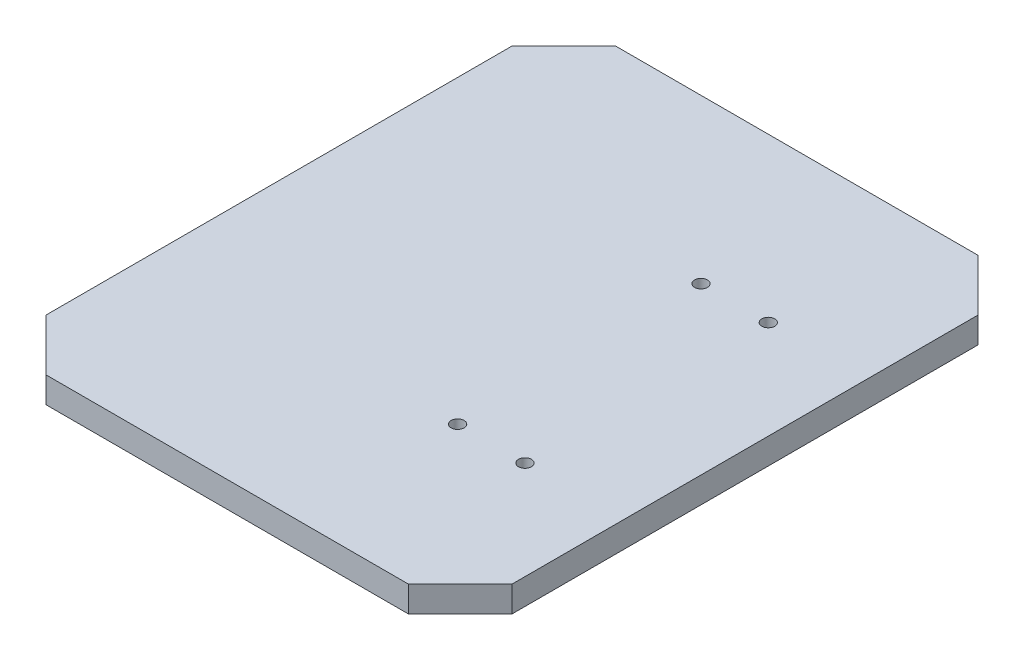
SolidWorks part; units mm, degrees
ref_plane "前视基准面" through (0, 0, 0) normal (0, 0, 1) x (1, 0, 0)
ref_plane "上视基准面" through (0, 0, 0) normal (0, 1, 0) x (1, 0, 0)
ref_plane "右视基准面" through (0, 0, 0) normal (1, 0, 0) x (0, 0, -1)
sketch "草图1" plane through (0, 0, 0) normal (0, 1, 0) x (1, 0, 0)
  line L0 (0, 0) -> (0, 110)
  line L1 (0, 110) -> (90, 110)
  line L2 (90, 110) -> (90, 0)
  line L3 (90, 0) -> (0, 0)
  line L4 (36, 110) -> (36, 0) construction
  line L5 (15, 110) -> (15, 0) construction
  line L6 (0, 55) -> (90, 55) construction
  point P11 (19, 78.5)
  point P12 (32, 78.5)
  point P16 (32, 31.5)
  point P17 (19, 31.5)
  dimension "D1" = 90
  dimension "D2" = 110
  dimension "D3" = 15
  dimension "D4" = 21
  dimension "D5" = 4
  dimension "D6" = 4
  dimension "D7" = 23.5
extrude "凸台-拉伸1" add sketch "草图1" along normal blind 5
chamfer "倒角1" distance 10 distance2 10 4 edges at (0, 2.5, -110) (90, 2.5, -110) (90, 2.5, 0) (0, 2.5, 0)
hole_wizard "M3 螺纹孔1" positions "草图2" profile "草图3" tap size "M3" standard "GB" end condition through all
sketch "草图2" plane through (0, 0, 0) normal (0, -1, 0) x (-1, 0, 0)
  line L1 (-90, 10) -> (-90, 100) construction
  line L2 (-90, 55) -> (0, 55) construction
  line L3 (0, 100) -> (0, 10) construction
  point P0 (-58, 78.5)
  point P2 (-58, 31.5)
  point P4 (-71, 31.5)
  point P6 (-71, 78.5)
  dimension "D1" = 19
  dimension "D2" = 13
  dimension "D3" = 23.5
  dimension "D4" = 23.5
cosmetic thread "孔螺蚊线1" parameters "D2"=3
cosmetic thread "孔螺蚊线2" parameters "D2"=3
cosmetic thread "孔螺蚊线3" parameters "D2"=3
cosmetic thread "孔螺蚊线4" parameters "D2"=3
sketch "草图3" plane through (58, 0, -78.5) normal (1, 0, 0) x (0, 0, -1)
  line L0 (0, 0) -> (0, 5)
  line L1 (0, 5) -> (1.25, 5)
  line L2 (1.25, 5) -> (1.25, 0)
  line L5 (1.25, 0) -> (0, 0)
  line L11 (0, -6.35) -> (0, 107.95) construction
  dimension "通孔螺纹孔钻头直径" = 2.5
  dimension "通孔螺纹孔钻头深度" = 5
